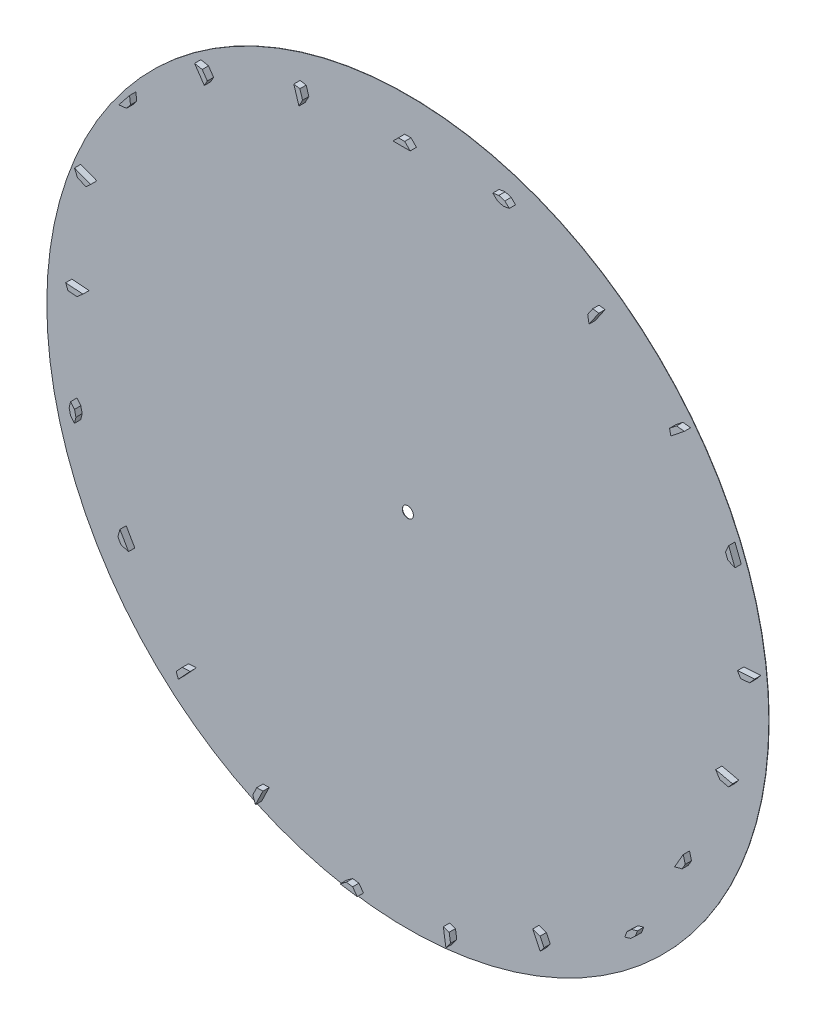
SolidWorks part; units mm, degrees
ref_plane "Front Plane" through (0, 0, 0) normal (0, 0, 1) x (1, 0, 0)
ref_plane "Top Plane" through (0, 0, 0) normal (0, 1, 0) x (1, 0, 0)
ref_plane "Right Plane" through (0, 0, 0) normal (1, 0, 0) x (0, 0, -1)
sketch "Sketch1" plane through (0, 0, 0) normal (0, 0, 1) x (1, 0, 0)
  line L0 (0, 0) -> (0, 115) construction
  circle A0 centre (0, 0) radius 115
  circle A1 centre (0, 0) radius 1.75
  dimension "D1" = 3.5
  dimension "D2" = 230
extrude "Boss-Extrude1" add sketch "Sketch1" along normal blind 0.1
sketch "Sketch2" plane through (0, 0, 0.1) normal (0, 0, 1) x (1, 0, 0)
  line L0 (0, 0) -> (0, 115) construction
  line L1 (0, 0) -> (6.8775, 114.7942) construction
  line L2 (0, 0) -> (13.7303, 114.1774) construction
  line L3 (0, 0) -> (20.534, 113.1519) construction
  line L4 (0, 0) -> (27.2642, 111.7214) construction
  line L5 (0, 0) -> (33.8968, 109.8909) construction
  line L6 (0, 0) -> (40.4081, 107.667) construction
  line L7 (0, 0) -> (46.7747, 105.0577) construction
  line L8 (0, 0) -> (52.9739, 102.0724) construction
  line L9 (0, 0) -> (58.9834, 98.7216) construction
  line L10 (0, 0) -> (64.7818, 95.0175) construction
  line L11 (0, 0) -> (70.3483, 90.9732) construction
  line L12 (0, 0) -> (75.663, 86.6032) construction
  line L13 (0, 0) -> (80.7068, 81.9233) construction
  line L14 (0, 0) -> (85.4617, 76.95) construction
  line L15 (0, 0) -> (89.9106, 71.7013) construction
  line L16 (0, 0) -> (94.0377, 66.196) construction
  line L17 (0, 0) -> (97.8282, 60.4536) construction
  line L18 (0, 0) -> (101.2685, 54.4949) construction
  line L19 (0, 0) -> (104.3462, 48.3411) construction
  line L20 (0, 0) -> (107.0505, 42.0142) construction
  line L21 (0, 0) -> (109.3715, 35.537) construction
  line L22 (0, 0) -> (111.301, 28.9325) construction
  line L23 (0, 0) -> (112.8321, 22.2244) construction
  line L24 (0, 0) -> (113.9592, 15.4368) construction
  line L25 (0, 0) -> (114.6784, 8.594) construction
  line L26 (0, 0) -> (114.9871, 1.7203) construction
  line L27 (0, 0) -> (114.8842, -5.1595) construction
  line L28 (0, 0) -> (114.37, -12.0208) construction
  line L29 (0, 0) -> (113.4464, -18.8391) construction
  line L30 (0, 0) -> (112.1167, -25.5899) construction
  line L31 (0, 0) -> (110.3857, -32.2491) construction
  line L32 (0, 0) -> (108.2594, -38.7929) construction
  line L33 (0, 0) -> (105.7457, -45.1979) construction
  line L34 (0, 0) -> (102.8534, -51.441) construction
  line L35 (0, 0) -> (99.5929, -57.5) construction
  line L36 (0, 0) -> (95.9759, -63.3532) construction
  line L37 (0, 0) -> (92.0154, -68.9795) construction
  line L38 (0, 0) -> (87.7254, -74.359) construction
  line L39 (0, 0) -> (83.1214, -79.4722) construction
  line L40 (0, 0) -> (78.2199, -84.301) construction
  line L41 (0, 0) -> (73.0383, -88.828) construction
  line L42 (0, 0) -> (67.5953, -93.037) construction
  line L43 (0, 0) -> (61.9103, -96.9129) construction
  line L44 (0, 0) -> (56.0037, -100.4419) construction
  line L45 (0, 0) -> (49.8966, -103.6114) construction
  line L46 (0, 0) -> (43.6109, -106.41) construction
  line L47 (0, 0) -> (37.1691, -108.8276) construction
  line L48 (0, 0) -> (30.5942, -110.8557) construction
  line L49 (0, 0) -> (23.9098, -112.487) construction
  line L50 (0, 0) -> (17.1399, -113.7155) construction
  line L51 (0, 0) -> (10.3085, -114.537) construction
  line L52 (0, 0) -> (3.4403, -114.9485) construction
  line L53 (0, 0) -> (-3.4403, -114.9485) construction
  line L54 (0, 0) -> (-10.3085, -114.537) construction
  line L55 (0, 0) -> (-17.1399, -113.7155) construction
  line L56 (0, 0) -> (-23.9098, -112.487) construction
  line L57 (0, 0) -> (-30.5942, -110.8557) construction
  line L58 (0, 0) -> (-37.1691, -108.8276) construction
  line L59 (0, 0) -> (-43.6109, -106.41) construction
  line L60 (0, 0) -> (-49.8966, -103.6114) construction
  line L61 (0, 0) -> (-56.0037, -100.4419) construction
  line L62 (0, 0) -> (-61.9103, -96.9129) construction
  line L63 (0, 0) -> (-67.5953, -93.037) construction
  line L64 (0, 0) -> (-73.0383, -88.828) construction
  line L65 (0, 0) -> (-78.2199, -84.301) construction
  line L66 (0, 0) -> (-83.1214, -79.4722) construction
  line L67 (0, 0) -> (-87.7254, -74.359) construction
  line L68 (0, 0) -> (-92.0154, -68.9795) construction
  line L69 (0, 0) -> (-95.9759, -63.3532) construction
  line L70 (0, 0) -> (-99.5929, -57.5) construction
  line L71 (0, 0) -> (-102.8534, -51.441) construction
  line L72 (0, 0) -> (-105.7457, -45.1979) construction
  line L73 (0, 0) -> (-108.2594, -38.7929) construction
  line L74 (0, 0) -> (-110.3857, -32.2491) construction
  line L75 (0, 0) -> (-112.1167, -25.5899) construction
  line L76 (0, 0) -> (-113.4464, -18.8391) construction
  line L77 (0, 0) -> (-114.37, -12.0208) construction
  line L78 (0, 0) -> (-114.8842, -5.1595) construction
  line L79 (0, 0) -> (-114.9871, 1.7203) construction
  line L80 (0, 0) -> (-114.6784, 8.594) construction
  line L81 (0, 0) -> (-113.9592, 15.4368) construction
  line L82 (0, 0) -> (-112.8321, 22.2244) construction
  line L83 (0, 0) -> (-111.301, 28.9325) construction
  line L84 (0, 0) -> (-109.3715, 35.537) construction
  line L85 (0, 0) -> (-107.0505, 42.0142) construction
  line L86 (0, 0) -> (-104.3462, 48.3411) construction
  line L87 (0, 0) -> (-101.2685, 54.4949) construction
  line L88 (0, 0) -> (-97.8282, 60.4536) construction
  line L89 (0, 0) -> (-94.0377, 66.196) construction
  line L90 (0, 0) -> (-89.9106, 71.7013) construction
  line L91 (0, 0) -> (-85.4617, 76.95) construction
  line L92 (0, 0) -> (-80.7068, 81.9233) construction
  line L93 (0, 0) -> (-75.663, 86.6032) construction
  line L94 (0, 0) -> (-70.3483, 90.9732) construction
  line L95 (0, 0) -> (-64.7818, 95.0175) construction
  line L96 (0, 0) -> (-58.9834, 98.7216) construction
  line L97 (0, 0) -> (-52.9739, 102.0724) construction
  line L98 (0, 0) -> (-46.7747, 105.0577) construction
  line L99 (0, 0) -> (-40.4081, 107.667) construction
  line L100 (0, 0) -> (-33.8968, 109.8909) construction
  line L101 (0, 0) -> (-27.2642, 111.7214) construction
  line L102 (0, 0) -> (-20.534, 113.1519) construction
  line L103 (0, 0) -> (-13.7303, 114.1774) construction
  line L104 (0, 0) -> (-6.8775, 114.7942) construction
  line L105 (-2.75, 113) -> (2.75, 113)
  line L106 (-2.75, 113) -> (2.75, 113) construction
  line L107 (-2.75, 113) -> (-2.75, 102) construction
  line L108 (-2.75, 102) -> (2.75, 102) construction
  line L109 (2.75, 113) -> (2.75, 102) construction
  line L110 (-1, 111.25) -> (1, 111.25) construction
  line L111 (-1, 111.25) -> (-1, 103.75) construction
  line L112 (-1, 103.75) -> (1, 103.75) construction
  line L113 (1, 111.25) -> (1, 103.75) construction
  line L114 (-1, 108.375) -> (1, 108.375) construction
  line L115 (-1, 108.375) -> (-1, 106.625) construction
  line L116 (-1, 106.625) -> (1, 106.625) construction
  line L117 (1, 108.375) -> (1, 106.625) construction
  line L118 (2.75, 113) -> (1, 111.25)
  line L119 (1, 111.25) -> (-1, 111.25)
  line L120 (-1, 111.25) -> (-2.75, 113)
  line L121 (-1, 108.375) -> (-2.75, 107.5)
  line L122 (-2.75, 107.5) -> (-1, 106.625)
  line L123 (-1, 106.625) -> (1, 106.625)
  line L124 (1, 106.625) -> (2.75, 107.5)
  line L125 (2.75, 107.5) -> (1, 108.375)
  line L126 (1, 108.375) -> (-1, 108.375)
  line L127 (-2.75, 113) -> (-2.75, 107.5)
  line L128 (-1, 111.25) -> (-1, 108.375)
  line L129 (1, 111.25) -> (1, 108.375)
  line L130 (2.75, 113) -> (2.75, 107.5)
  line L131 (-1, 103.75) -> (-2.75, 102)
  line L132 (-2.75, 102) -> (2.75, 102)
  line L133 (2.75, 102) -> (1, 103.75)
  line L134 (1, 103.75) -> (-1, 103.75)
  line L135 (-1, 103.75) -> (-1, 106.625)
  line L136 (-2.75, 107.5) -> (-2.75, 102)
  line L137 (2.75, 107.5) -> (2.75, 102)
  line L138 (1, 106.625) -> (1, 103.75)
  line L139 (30.6795, 108.7903) -> (35.9352, 107.1692)
  line L140 (31.8359, 106.6022) -> (30.6795, 108.7903)
  line L141 (35.9352, 107.1692) -> (33.7471, 106.0127)
  line L142 (33.7471, 106.0127) -> (31.8359, 106.6022)
  line L143 (31.8359, 106.6022) -> (30.9885, 103.855)
  line L144 (30.6795, 108.7903) -> (29.0584, 103.5347)
  line L145 (30.9885, 103.855) -> (29.0584, 103.5347)
  line L146 (29.0584, 103.5347) -> (27.4372, 98.279)
  line L147 (29.0584, 103.5347) -> (30.4727, 102.1827)
  line L148 (29.6253, 99.4354) -> (27.4372, 98.279)
  line L149 (27.4372, 98.279) -> (32.6929, 96.6578)
  line L150 (31.5364, 98.8459) -> (29.6253, 99.4354)
  line L151 (32.6929, 96.6578) -> (31.5364, 98.8459)
  line L152 (34.314, 101.9135) -> (32.6929, 96.6578)
  line L153 (30.4727, 102.1827) -> (32.3838, 101.5932)
  line L154 (29.6253, 99.4354) -> (30.4727, 102.1827)
  line L155 (32.3838, 101.5932) -> (31.5364, 98.8459)
  line L156 (32.3838, 101.5932) -> (34.314, 101.9135)
  line L157 (34.314, 101.9135) -> (32.8997, 103.2654)
  line L158 (35.9352, 107.1692) -> (34.314, 101.9135)
  line L159 (33.7471, 106.0127) -> (32.8997, 103.2654)
  line L160 (32.8997, 103.2654) -> (30.9885, 103.855)
  line L161 (61.383, 94.9141) -> (65.9273, 91.8159)
  line L162 (61.8431, 92.4824) -> (61.383, 94.9141)
  line L163 (65.9273, 91.8159) -> (63.4956, 91.3557)
  line L164 (63.4956, 91.3557) -> (61.8431, 92.4824)
  line L165 (61.8431, 92.4824) -> (60.2236, 90.1069)
  line L166 (61.383, 94.9141) -> (58.2847, 90.3698)
  line L167 (60.2236, 90.1069) -> (58.2847, 90.3698)
  line L168 (58.2847, 90.3698) -> (55.1865, 85.8255)
  line L169 (58.2847, 90.3698) -> (59.2378, 88.661)
  line L170 (57.6182, 86.2856) -> (55.1865, 85.8255)
  line L171 (55.1865, 85.8255) -> (59.7308, 82.7272)
  line L172 (59.2707, 85.159) -> (57.6182, 86.2856)
  line L173 (59.7308, 82.7272) -> (59.2707, 85.159)
  line L174 (62.8291, 87.2715) -> (59.7308, 82.7272)
  line L175 (59.2378, 88.661) -> (60.8902, 87.5344)
  line L176 (57.6182, 86.2856) -> (59.2378, 88.661)
  line L177 (60.8902, 87.5344) -> (59.2707, 85.159)
  line L178 (60.8902, 87.5344) -> (62.8291, 87.2715)
  line L179 (62.8291, 87.2715) -> (61.8761, 88.9803)
  line L180 (65.9273, 91.8159) -> (62.8291, 87.2715)
  line L181 (63.4956, 91.3557) -> (61.8761, 88.9803)
  line L182 (61.8761, 88.9803) -> (60.2236, 90.1069)
  line L183 (86.6324, 72.6044) -> (90.0616, 68.3043)
  line L184 (86.3553, 70.1451) -> (86.6324, 72.6044)
  line L185 (90.0616, 68.3043) -> (87.6022, 68.5814)
  line L186 (87.6022, 68.5814) -> (86.3553, 70.1451)
  line L187 (86.3553, 70.1451) -> (84.1075, 68.3525)
  line L188 (86.6324, 72.6044) -> (82.3323, 69.1752)
  line L189 (84.1075, 68.3525) -> (82.3323, 69.1752)
  line L190 (82.3323, 69.1752) -> (78.0322, 65.746)
  line L191 (82.3323, 69.1752) -> (82.7393, 67.2614)
  line L192 (80.4915, 65.4689) -> (78.0322, 65.746)
  line L193 (78.0322, 65.746) -> (81.4614, 61.4459)
  line L194 (81.7385, 63.9052) -> (80.4915, 65.4689)
  line L195 (81.4614, 61.4459) -> (81.7385, 63.9052)
  line L196 (85.7615, 64.8751) -> (81.4614, 61.4459)
  line L197 (82.7393, 67.2614) -> (83.9863, 65.6978)
  line L198 (80.4915, 65.4689) -> (82.7393, 67.2614)
  line L199 (83.9863, 65.6978) -> (81.7385, 63.9052)
  line L200 (83.9863, 65.6978) -> (85.7615, 64.8751)
  line L201 (85.7615, 64.8751) -> (85.3545, 66.7889)
  line L202 (90.0616, 68.3043) -> (85.7615, 64.8751)
  line L203 (87.6022, 68.5814) -> (85.3545, 66.7889)
  line L204 (85.3545, 66.7889) -> (84.1075, 68.3525)
  line L205 (104.184, 43.8434) -> (106.1934, 38.7236)
  line L206 (103.1944, 41.5751) -> (104.184, 43.8434)
  line L207 (106.1934, 38.7236) -> (103.925, 39.7133)
  line L208 (103.925, 39.7133) -> (103.1944, 41.5751)
  line L209 (103.1944, 41.5751) -> (100.5181, 40.5247)
  line L210 (104.184, 43.8434) -> (99.0642, 41.8341)
  line L211 (100.5181, 40.5247) -> (99.0642, 41.8341)
  line L212 (99.0642, 41.8341) -> (93.9444, 39.8247)
  line L213 (99.0642, 41.8341) -> (98.8891, 39.8854)
  line L214 (96.2128, 38.835) -> (93.9444, 39.8247)
  line L215 (93.9444, 39.8247) -> (95.9538, 34.7049)
  line L216 (96.9435, 36.9733) -> (96.2128, 38.835)
  line L217 (95.9538, 34.7049) -> (96.9435, 36.9733)
  line L218 (101.0736, 36.7143) -> (95.9538, 34.7049)
  line L219 (98.8891, 39.8854) -> (99.6198, 38.0236)
  line L220 (96.2128, 38.835) -> (98.8891, 39.8854)
  line L221 (99.6198, 38.0236) -> (96.9435, 36.9733)
  line L222 (99.6198, 38.0236) -> (101.0736, 36.7143)
  line L223 (101.0736, 36.7143) -> (101.2488, 38.663)
  line L224 (106.1934, 38.7236) -> (101.0736, 36.7143)
  line L225 (103.925, 39.7133) -> (101.2488, 38.663)
  line L226 (101.2488, 38.663) -> (100.5181, 40.5247)
  line L227 (112.4785, 11.1868) -> (112.8895, 5.7022)
  line L228 (110.8642, 9.3109) -> (112.4785, 11.1868)
  line L229 (112.8895, 5.7022) -> (111.0137, 7.3165)
  line L230 (111.0137, 7.3165) -> (110.8642, 9.3109)
  line L231 (110.8642, 9.3109) -> (107.9972, 9.0961)
  line L232 (112.4785, 11.1868) -> (106.9939, 10.7758)
  line L233 (107.9972, 9.0961) -> (106.9939, 10.7758)
  line L234 (106.9939, 10.7758) -> (101.5093, 10.3648)
  line L235 (106.9939, 10.7758) -> (106.2521, 8.9653)
  line L236 (103.3852, 8.7505) -> (101.5093, 10.3648)
  line L237 (101.5093, 10.3648) -> (101.9203, 4.8802)
  line L238 (103.5346, 6.756) -> (103.3852, 8.7505)
  line L239 (101.9203, 4.8802) -> (103.5346, 6.756)
  line L240 (107.4049, 5.2912) -> (101.9203, 4.8802)
  line L241 (106.2521, 8.9653) -> (106.4016, 6.9709)
  line L242 (103.3852, 8.7505) -> (106.2521, 8.9653)
  line L243 (106.4016, 6.9709) -> (103.5346, 6.756)
  line L244 (106.4016, 6.9709) -> (107.4049, 5.2912)
  line L245 (107.4049, 5.2912) -> (108.1467, 7.1017)
  line L246 (112.8895, 5.7022) -> (107.4049, 5.2912)
  line L247 (111.0137, 7.3165) -> (108.1467, 7.1017)
  line L248 (108.1467, 7.1017) -> (107.9972, 9.0961)
  line L249 (110.7788, -22.4638) -> (109.5549, -27.8259)
  line L250 (108.6833, -23.7805) -> (110.7788, -22.4638)
  line L251 (109.5549, -27.8259) -> (108.2382, -25.7304)
  line L252 (108.2382, -25.7304) -> (108.6833, -23.7805)
  line L253 (108.6833, -23.7805) -> (105.8803, -23.1408)
  line L254 (110.7788, -22.4638) -> (105.4167, -21.2399)
  line L255 (105.8803, -23.1408) -> (105.4167, -21.2399)
  line L256 (105.4167, -21.2399) -> (100.0546, -20.0161)
  line L257 (105.4167, -21.2399) -> (104.1742, -22.7514)
  line L258 (101.3713, -22.1116) -> (100.0546, -20.0161)
  line L259 (100.0546, -20.0161) -> (98.8307, -25.3782)
  line L260 (100.9262, -24.0615) -> (101.3713, -22.1116)
  line L261 (98.8307, -25.3782) -> (100.9262, -24.0615)
  line L262 (104.1928, -26.6021) -> (98.8307, -25.3782)
  line L263 (104.1742, -22.7514) -> (103.7292, -24.7012)
  line L264 (101.3713, -22.1116) -> (104.1742, -22.7514)
  line L265 (103.7292, -24.7012) -> (100.9262, -24.0615)
  line L266 (103.7292, -24.7012) -> (104.1928, -26.6021)
  line L267 (104.1928, -26.6021) -> (105.4353, -25.0906)
  line L268 (109.5549, -27.8259) -> (104.1928, -26.6021)
  line L269 (108.2382, -25.7304) -> (105.4353, -25.0906)
  line L270 (105.4353, -25.0906) -> (105.8803, -23.1408)
  line L271 (99.2359, -54.1184) -> (96.4859, -58.8816)
  line L272 (96.8453, -54.759) -> (99.2359, -54.1184)
  line L273 (96.4859, -58.8816) -> (95.8453, -56.491)
  line L274 (95.8453, -56.491) -> (96.8453, -54.759)
  line L275 (96.8453, -54.759) -> (94.3555, -53.3215)
  line L276 (99.2359, -54.1184) -> (94.4727, -51.3684)
  line L277 (94.3555, -53.3215) -> (94.4727, -51.3684)
  line L278 (94.4727, -51.3684) -> (89.7096, -48.6184)
  line L279 (94.4727, -51.3684) -> (92.84, -52.4465)
  line L280 (90.3501, -51.009) -> (89.7096, -48.6184)
  line L281 (89.7096, -48.6184) -> (86.9596, -53.3816)
  line L282 (89.3501, -52.741) -> (90.3501, -51.009)
  line L283 (86.9596, -53.3816) -> (89.3501, -52.741)
  line L284 (91.7227, -56.1316) -> (86.9596, -53.3816)
  line L285 (92.84, -52.4465) -> (91.84, -54.1785)
  line L286 (90.3501, -51.009) -> (92.84, -52.4465)
  line L287 (91.84, -54.1785) -> (89.3501, -52.741)
  line L288 (91.84, -54.1785) -> (91.7227, -56.1316)
  line L289 (91.7227, -56.1316) -> (93.3555, -55.0535)
  line L290 (96.4859, -58.8816) -> (91.7227, -56.1316)
  line L291 (95.8453, -56.491) -> (93.3555, -55.0535)
  line L292 (93.3555, -55.0535) -> (94.3555, -53.3215)
  line L293 (78.8754, -80.9644) -> (74.8436, -84.7053)
  line L294 (76.4023, -80.8718) -> (78.8754, -80.9644)
  line L295 (74.8436, -84.7053) -> (74.9362, -82.2322)
  line L296 (74.9362, -82.2322) -> (76.4023, -80.8718)
  line L297 (76.4023, -80.8718) -> (74.4468, -78.7643)
  line L298 (78.8754, -80.9644) -> (75.1345, -76.9326)
  line L299 (74.4468, -78.7643) -> (75.1345, -76.9326)
  line L300 (75.1345, -76.9326) -> (71.3935, -72.9008)
  line L301 (75.1345, -76.9326) -> (73.2565, -77.4815)
  line L302 (71.301, -75.374) -> (71.3935, -72.9008)
  line L303 (71.3935, -72.9008) -> (67.3617, -76.6418)
  line L304 (69.8349, -76.7343) -> (71.301, -75.374)
  line L305 (67.3617, -76.6418) -> (69.8349, -76.7343)
  line L306 (71.1027, -80.6736) -> (67.3617, -76.6418)
  line L307 (73.2565, -77.4815) -> (71.7904, -78.8418)
  line L308 (71.301, -75.374) -> (73.2565, -77.4815)
  line L309 (71.7904, -78.8418) -> (69.8349, -76.7343)
  line L310 (71.7904, -78.8418) -> (71.1027, -80.6736)
  line L311 (71.1027, -80.6736) -> (72.9807, -80.1247)
  line L312 (74.8436, -84.7053) -> (71.1027, -80.6736)
  line L313 (74.9362, -82.2322) -> (72.9807, -80.1247)
  line L314 (72.9807, -80.1247) -> (74.4468, -78.7643)
  line L315 (51.5065, -100.6163) -> (46.5512, -103.0027)
  line L316 (49.1705, -99.7989) -> (51.5065, -100.6163)
  line L317 (46.5512, -103.0027) -> (47.3686, -100.6667)
  line L318 (47.3686, -100.6667) -> (49.1705, -99.7989)
  line L319 (49.1705, -99.7989) -> (47.9231, -97.2086)
  line L320 (51.5065, -100.6163) -> (49.1202, -95.661)
  line L321 (47.9231, -97.2086) -> (49.1202, -95.661)
  line L322 (49.1202, -95.661) -> (46.7338, -90.7056)
  line L323 (49.1202, -95.661) -> (47.1638, -95.6319)
  line L324 (45.9164, -93.0416) -> (46.7338, -90.7056)
  line L325 (46.7338, -90.7056) -> (41.7785, -93.092)
  line L326 (44.1145, -93.9094) -> (45.9164, -93.0416)
  line L327 (41.7785, -93.092) -> (44.1145, -93.9094)
  line L328 (44.1648, -98.0473) -> (41.7785, -93.092)
  line L329 (47.1638, -95.6319) -> (45.3619, -96.4997)
  line L330 (45.9164, -93.0416) -> (47.1638, -95.6319)
  line L331 (45.3619, -96.4997) -> (44.1145, -93.9094)
  line L332 (45.3619, -96.4997) -> (44.1648, -98.0473)
  line L333 (44.1648, -98.0473) -> (46.1212, -98.0764)
  line L334 (46.5512, -103.0027) -> (44.1648, -98.0473)
  line L335 (47.3686, -100.6667) -> (46.1212, -98.0764)
  line L336 (46.1212, -98.0764) -> (47.9231, -97.2086)
  line L337 (19.5611, -111.328) -> (14.1225, -112.1477)
  line L338 (17.5698, -109.8584) -> (19.5611, -111.328)
  line L339 (14.1225, -112.1477) -> (15.5921, -110.1565)
  line L340 (15.5921, -110.1565) -> (17.5698, -109.8584)
  line L341 (17.5698, -109.8584) -> (17.1413, -107.0155)
  line L342 (19.5611, -111.328) -> (18.7413, -105.8894)
  line L343 (17.1413, -107.0155) -> (18.7413, -105.8894)
  line L344 (18.7413, -105.8894) -> (17.9216, -100.4509)
  line L345 (18.7413, -105.8894) -> (16.8805, -105.285)
  line L346 (16.452, -102.4422) -> (17.9216, -100.4509)
  line L347 (17.9216, -100.4509) -> (12.483, -101.2706)
  line L348 (14.4743, -102.7402) -> (16.452, -102.4422)
  line L349 (12.483, -101.2706) -> (14.4743, -102.7402)
  line L350 (13.3028, -106.7092) -> (12.483, -101.2706)
  line L351 (16.8805, -105.285) -> (14.9028, -105.5831)
  line L352 (16.452, -102.4422) -> (16.8805, -105.285)
  line L353 (14.9028, -105.5831) -> (14.4743, -102.7402)
  line L354 (14.9028, -105.5831) -> (13.3028, -106.7092)
  line L355 (13.3028, -106.7092) -> (15.1636, -107.3136)
  line L356 (14.1225, -112.1477) -> (13.3028, -106.7092)
  line L357 (15.5921, -110.1565) -> (15.1636, -107.3136)
  line L358 (15.1636, -107.3136) -> (17.1413, -107.0155)
  line L359 (-14.1225, -112.1477) -> (-19.5611, -111.328)
  line L360 (-15.5921, -110.1565) -> (-14.1225, -112.1477)
  line L361 (-19.5611, -111.328) -> (-17.5698, -109.8584)
  line L362 (-17.5698, -109.8584) -> (-15.5921, -110.1565)
  line L363 (-15.5921, -110.1565) -> (-15.1636, -107.3136)
  line L364 (-14.1225, -112.1477) -> (-13.3028, -106.7092)
  line L365 (-15.1636, -107.3136) -> (-13.3028, -106.7092)
  line L366 (-13.3028, -106.7092) -> (-12.483, -101.2706)
  line L367 (-13.3028, -106.7092) -> (-14.9028, -105.5831)
  line L368 (-14.4743, -102.7402) -> (-12.483, -101.2706)
  line L369 (-12.483, -101.2706) -> (-17.9216, -100.4509)
  line L370 (-16.452, -102.4422) -> (-14.4743, -102.7402)
  line L371 (-17.9216, -100.4509) -> (-16.452, -102.4422)
  line L372 (-18.7413, -105.8894) -> (-17.9216, -100.4509)
  line L373 (-14.9028, -105.5831) -> (-16.8805, -105.285)
  line L374 (-14.4743, -102.7402) -> (-14.9028, -105.5831)
  line L375 (-16.8805, -105.285) -> (-16.452, -102.4422)
  line L376 (-16.8805, -105.285) -> (-18.7413, -105.8894)
  line L377 (-18.7413, -105.8894) -> (-17.1413, -107.0155)
  line L378 (-19.5611, -111.328) -> (-18.7413, -105.8894)
  line L379 (-17.5698, -109.8584) -> (-17.1413, -107.0155)
  line L380 (-17.1413, -107.0155) -> (-15.1636, -107.3136)
  line L381 (-46.5512, -103.0027) -> (-51.5065, -100.6163)
  line L382 (-47.3686, -100.6667) -> (-46.5512, -103.0027)
  line L383 (-51.5065, -100.6163) -> (-49.1705, -99.7989)
  line L384 (-49.1705, -99.7989) -> (-47.3686, -100.6667)
  line L385 (-47.3686, -100.6667) -> (-46.1212, -98.0764)
  line L386 (-46.5512, -103.0027) -> (-44.1648, -98.0473)
  line L387 (-46.1212, -98.0764) -> (-44.1648, -98.0473)
  line L388 (-44.1648, -98.0473) -> (-41.7785, -93.092)
  line L389 (-44.1648, -98.0473) -> (-45.3619, -96.4997)
  line L390 (-44.1145, -93.9094) -> (-41.7785, -93.092)
  line L391 (-41.7785, -93.092) -> (-46.7338, -90.7056)
  line L392 (-45.9164, -93.0416) -> (-44.1145, -93.9094)
  line L393 (-46.7338, -90.7056) -> (-45.9164, -93.0416)
  line L394 (-49.1202, -95.661) -> (-46.7338, -90.7056)
  line L395 (-45.3619, -96.4997) -> (-47.1638, -95.6319)
  line L396 (-44.1145, -93.9094) -> (-45.3619, -96.4997)
  line L397 (-47.1638, -95.6319) -> (-45.9164, -93.0416)
  line L398 (-47.1638, -95.6319) -> (-49.1202, -95.661)
  line L399 (-49.1202, -95.661) -> (-47.9231, -97.2086)
  line L400 (-51.5065, -100.6163) -> (-49.1202, -95.661)
  line L401 (-49.1705, -99.7989) -> (-47.9231, -97.2086)
  line L402 (-47.9231, -97.2086) -> (-46.1212, -98.0764)
  line L403 (-74.8436, -84.7053) -> (-78.8754, -80.9644)
  line L404 (-74.9362, -82.2322) -> (-74.8436, -84.7053)
  line L405 (-78.8754, -80.9644) -> (-76.4023, -80.8718)
  line L406 (-76.4023, -80.8718) -> (-74.9362, -82.2322)
  line L407 (-74.9362, -82.2322) -> (-72.9807, -80.1247)
  line L408 (-74.8436, -84.7053) -> (-71.1027, -80.6736)
  line L409 (-72.9807, -80.1247) -> (-71.1027, -80.6736)
  line L410 (-71.1027, -80.6736) -> (-67.3617, -76.6418)
  line L411 (-71.1027, -80.6736) -> (-71.7904, -78.8418)
  line L412 (-69.8349, -76.7343) -> (-67.3617, -76.6418)
  line L413 (-67.3617, -76.6418) -> (-71.3935, -72.9008)
  line L414 (-71.301, -75.374) -> (-69.8349, -76.7343)
  line L415 (-71.3935, -72.9008) -> (-71.301, -75.374)
  line L416 (-75.1345, -76.9326) -> (-71.3935, -72.9008)
  line L417 (-71.7904, -78.8418) -> (-73.2565, -77.4815)
  line L418 (-69.8349, -76.7343) -> (-71.7904, -78.8418)
  line L419 (-73.2565, -77.4815) -> (-71.301, -75.374)
  line L420 (-73.2565, -77.4815) -> (-75.1345, -76.9326)
  line L421 (-75.1345, -76.9326) -> (-74.4468, -78.7643)
  line L422 (-78.8754, -80.9644) -> (-75.1345, -76.9326)
  line L423 (-76.4023, -80.8718) -> (-74.4468, -78.7643)
  line L424 (-74.4468, -78.7643) -> (-72.9807, -80.1247)
  line L425 (-96.4859, -58.8816) -> (-99.2359, -54.1184)
  line L426 (-95.8453, -56.491) -> (-96.4859, -58.8816)
  line L427 (-99.2359, -54.1184) -> (-96.8453, -54.759)
  line L428 (-96.8453, -54.759) -> (-95.8453, -56.491)
  line L429 (-95.8453, -56.491) -> (-93.3555, -55.0535)
  line L430 (-96.4859, -58.8816) -> (-91.7227, -56.1316)
  line L431 (-93.3555, -55.0535) -> (-91.7227, -56.1316)
  line L432 (-91.7227, -56.1316) -> (-86.9596, -53.3816)
  line L433 (-91.7227, -56.1316) -> (-91.84, -54.1785)
  line L434 (-89.3501, -52.741) -> (-86.9596, -53.3816)
  line L435 (-86.9596, -53.3816) -> (-89.7096, -48.6184)
  line L436 (-90.3501, -51.009) -> (-89.3501, -52.741)
  line L437 (-89.7096, -48.6184) -> (-90.3501, -51.009)
  line L438 (-94.4727, -51.3684) -> (-89.7096, -48.6184)
  line L439 (-91.84, -54.1785) -> (-92.84, -52.4465)
  line L440 (-89.3501, -52.741) -> (-91.84, -54.1785)
  line L441 (-92.84, -52.4465) -> (-90.3501, -51.009)
  line L442 (-92.84, -52.4465) -> (-94.4727, -51.3684)
  line L443 (-94.4727, -51.3684) -> (-94.3555, -53.3215)
  line L444 (-99.2359, -54.1184) -> (-94.4727, -51.3684)
  line L445 (-96.8453, -54.759) -> (-94.3555, -53.3215)
  line L446 (-94.3555, -53.3215) -> (-93.3555, -55.0535)
  line L447 (-109.5549, -27.8259) -> (-110.7788, -22.4638)
  line L448 (-108.2382, -25.7304) -> (-109.5549, -27.8259)
  line L449 (-110.7788, -22.4638) -> (-108.6833, -23.7805)
  line L450 (-108.6833, -23.7805) -> (-108.2382, -25.7304)
  line L451 (-108.2382, -25.7304) -> (-105.4353, -25.0906)
  line L452 (-109.5549, -27.8259) -> (-104.1928, -26.6021)
  line L453 (-105.4353, -25.0906) -> (-104.1928, -26.6021)
  line L454 (-104.1928, -26.6021) -> (-98.8307, -25.3782)
  line L455 (-104.1928, -26.6021) -> (-103.7292, -24.7012)
  line L456 (-100.9262, -24.0615) -> (-98.8307, -25.3782)
  line L457 (-98.8307, -25.3782) -> (-100.0546, -20.0161)
  line L458 (-101.3713, -22.1116) -> (-100.9262, -24.0615)
  line L459 (-100.0546, -20.0161) -> (-101.3713, -22.1116)
  line L460 (-105.4167, -21.2399) -> (-100.0546, -20.0161)
  line L461 (-103.7292, -24.7012) -> (-104.1742, -22.7514)
  line L462 (-100.9262, -24.0615) -> (-103.7292, -24.7012)
  line L463 (-104.1742, -22.7514) -> (-101.3713, -22.1116)
  line L464 (-104.1742, -22.7514) -> (-105.4167, -21.2399)
  line L465 (-105.4167, -21.2399) -> (-105.8803, -23.1408)
  line L466 (-110.7788, -22.4638) -> (-105.4167, -21.2399)
  line L467 (-108.6833, -23.7805) -> (-105.8803, -23.1408)
  line L468 (-105.8803, -23.1408) -> (-105.4353, -25.0906)
  line L469 (-112.8895, 5.7022) -> (-112.4785, 11.1868)
  line L470 (-111.0137, 7.3165) -> (-112.8895, 5.7022)
  line L471 (-112.4785, 11.1868) -> (-110.8642, 9.3109)
  line L472 (-110.8642, 9.3109) -> (-111.0137, 7.3165)
  line L473 (-111.0137, 7.3165) -> (-108.1467, 7.1017)
  line L474 (-112.8895, 5.7022) -> (-107.4049, 5.2912)
  line L475 (-108.1467, 7.1017) -> (-107.4049, 5.2912)
  line L476 (-107.4049, 5.2912) -> (-101.9203, 4.8802)
  line L477 (-107.4049, 5.2912) -> (-106.4016, 6.9709)
  line L478 (-103.5346, 6.756) -> (-101.9203, 4.8802)
  line L479 (-101.9203, 4.8802) -> (-101.5093, 10.3648)
  line L480 (-103.3852, 8.7505) -> (-103.5346, 6.756)
  line L481 (-101.5093, 10.3648) -> (-103.3852, 8.7505)
  line L482 (-106.9939, 10.7758) -> (-101.5093, 10.3648)
  line L483 (-106.4016, 6.9709) -> (-106.2521, 8.9653)
  line L484 (-103.5346, 6.756) -> (-106.4016, 6.9709)
  line L485 (-106.2521, 8.9653) -> (-103.3852, 8.7505)
  line L486 (-106.2521, 8.9653) -> (-106.9939, 10.7758)
  line L487 (-106.9939, 10.7758) -> (-107.9972, 9.0961)
  line L488 (-112.4785, 11.1868) -> (-106.9939, 10.7758)
  line L489 (-110.8642, 9.3109) -> (-107.9972, 9.0961)
  line L490 (-107.9972, 9.0961) -> (-108.1467, 7.1017)
  line L491 (-106.1934, 38.7236) -> (-104.184, 43.8434)
  line L492 (-103.925, 39.7133) -> (-106.1934, 38.7236)
  line L493 (-104.184, 43.8434) -> (-103.1944, 41.5751)
  line L494 (-103.1944, 41.5751) -> (-103.925, 39.7133)
  line L495 (-103.925, 39.7133) -> (-101.2488, 38.663)
  line L496 (-106.1934, 38.7236) -> (-101.0736, 36.7143)
  line L497 (-101.2488, 38.663) -> (-101.0736, 36.7143)
  line L498 (-101.0736, 36.7143) -> (-95.9538, 34.7049)
  line L499 (-101.0736, 36.7143) -> (-99.6198, 38.0236)
  line L500 (-96.9435, 36.9733) -> (-95.9538, 34.7049)
  line L501 (-95.9538, 34.7049) -> (-93.9444, 39.8247)
  line L502 (-96.2128, 38.835) -> (-96.9435, 36.9733)
  line L503 (-93.9444, 39.8247) -> (-96.2128, 38.835)
  line L504 (-99.0642, 41.8341) -> (-93.9444, 39.8247)
  line L505 (-99.6198, 38.0236) -> (-98.8891, 39.8854)
  line L506 (-96.9435, 36.9733) -> (-99.6198, 38.0236)
  line L507 (-98.8891, 39.8854) -> (-96.2128, 38.835)
  line L508 (-98.8891, 39.8854) -> (-99.0642, 41.8341)
  line L509 (-99.0642, 41.8341) -> (-100.5181, 40.5247)
  line L510 (-104.184, 43.8434) -> (-99.0642, 41.8341)
  line L511 (-103.1944, 41.5751) -> (-100.5181, 40.5247)
  line L512 (-100.5181, 40.5247) -> (-101.2488, 38.663)
  line L513 (-90.0616, 68.3043) -> (-86.6324, 72.6044)
  line L514 (-87.6022, 68.5814) -> (-90.0616, 68.3043)
  line L515 (-86.6324, 72.6044) -> (-86.3553, 70.1451)
  line L516 (-86.3553, 70.1451) -> (-87.6022, 68.5814)
  line L517 (-87.6022, 68.5814) -> (-85.3545, 66.7889)
  line L518 (-90.0616, 68.3043) -> (-85.7615, 64.8751)
  line L519 (-85.3545, 66.7889) -> (-85.7615, 64.8751)
  line L520 (-85.7615, 64.8751) -> (-81.4614, 61.4459)
  line L521 (-85.7615, 64.8751) -> (-83.9863, 65.6978)
  line L522 (-81.7385, 63.9052) -> (-81.4614, 61.4459)
  line L523 (-81.4614, 61.4459) -> (-78.0322, 65.746)
  line L524 (-80.4915, 65.4689) -> (-81.7385, 63.9052)
  line L525 (-78.0322, 65.746) -> (-80.4915, 65.4689)
  line L526 (-82.3323, 69.1752) -> (-78.0322, 65.746)
  line L527 (-83.9863, 65.6978) -> (-82.7393, 67.2614)
  line L528 (-81.7385, 63.9052) -> (-83.9863, 65.6978)
  line L529 (-82.7393, 67.2614) -> (-80.4915, 65.4689)
  line L530 (-82.7393, 67.2614) -> (-82.3323, 69.1752)
  line L531 (-82.3323, 69.1752) -> (-84.1075, 68.3525)
  line L532 (-86.6324, 72.6044) -> (-82.3323, 69.1752)
  line L533 (-86.3553, 70.1451) -> (-84.1075, 68.3525)
  line L534 (-84.1075, 68.3525) -> (-85.3545, 66.7889)
  line L535 (-65.9273, 91.8159) -> (-61.383, 94.9141)
  line L536 (-63.4956, 91.3557) -> (-65.9273, 91.8159)
  line L537 (-61.383, 94.9141) -> (-61.8431, 92.4824)
  line L538 (-61.8431, 92.4824) -> (-63.4956, 91.3557)
  line L539 (-63.4956, 91.3557) -> (-61.8761, 88.9803)
  line L540 (-65.9273, 91.8159) -> (-62.8291, 87.2715)
  line L541 (-61.8761, 88.9803) -> (-62.8291, 87.2715)
  line L542 (-62.8291, 87.2715) -> (-59.7308, 82.7272)
  line L543 (-62.8291, 87.2715) -> (-60.8902, 87.5344)
  line L544 (-59.2707, 85.159) -> (-59.7308, 82.7272)
  line L545 (-59.7308, 82.7272) -> (-55.1865, 85.8255)
  line L546 (-57.6182, 86.2856) -> (-59.2707, 85.159)
  line L547 (-55.1865, 85.8255) -> (-57.6182, 86.2856)
  line L548 (-58.2847, 90.3698) -> (-55.1865, 85.8255)
  line L549 (-60.8902, 87.5344) -> (-59.2378, 88.661)
  line L550 (-59.2707, 85.159) -> (-60.8902, 87.5344)
  line L551 (-59.2378, 88.661) -> (-57.6182, 86.2856)
  line L552 (-59.2378, 88.661) -> (-58.2847, 90.3698)
  line L553 (-58.2847, 90.3698) -> (-60.2236, 90.1069)
  line L554 (-61.383, 94.9141) -> (-58.2847, 90.3698)
  line L555 (-61.8431, 92.4824) -> (-60.2236, 90.1069)
  line L556 (-60.2236, 90.1069) -> (-61.8761, 88.9803)
  line L557 (-35.9352, 107.1692) -> (-30.6795, 108.7903)
  line L558 (-33.7471, 106.0127) -> (-35.9352, 107.1692)
  line L559 (-30.6795, 108.7903) -> (-31.8359, 106.6022)
  line L560 (-31.8359, 106.6022) -> (-33.7471, 106.0127)
  line L561 (-33.7471, 106.0127) -> (-32.8997, 103.2654)
  line L562 (-35.9352, 107.1692) -> (-34.314, 101.9135)
  line L563 (-32.8997, 103.2654) -> (-34.314, 101.9135)
  line L564 (-34.314, 101.9135) -> (-32.6929, 96.6578)
  line L565 (-34.314, 101.9135) -> (-32.3838, 101.5932)
  line L566 (-31.5364, 98.8459) -> (-32.6929, 96.6578)
  line L567 (-32.6929, 96.6578) -> (-27.4372, 98.279)
  line L568 (-29.6253, 99.4354) -> (-31.5364, 98.8459)
  line L569 (-27.4372, 98.279) -> (-29.6253, 99.4354)
  line L570 (-29.0584, 103.5347) -> (-27.4372, 98.279)
  line L571 (-32.3838, 101.5932) -> (-30.4727, 102.1827)
  line L572 (-31.5364, 98.8459) -> (-32.3838, 101.5932)
  line L573 (-30.4727, 102.1827) -> (-29.6253, 99.4354)
  line L574 (-30.4727, 102.1827) -> (-29.0584, 103.5347)
  line L575 (-29.0584, 103.5347) -> (-30.9885, 103.855)
  line L576 (-30.6795, 108.7903) -> (-29.0584, 103.5347)
  line L577 (-31.8359, 106.6022) -> (-30.9885, 103.855)
  line L578 (-30.9885, 103.855) -> (-32.8997, 103.2654)
  circle A0 centre (0, 0) radius 115 construction
  point P111 (0, 0)
  point P115 (0, 102)
  point P124 (1, 107.5)
  point P125 (1, 107.5)
  point P411 (0, 0)
  dimension "D2" = 5.5
  dimension "D3" = 11
  dimension "D4" = 102
  dimension "D5" = 1.75
  dimension "D6" = 1.75
  dimension "D7" = 1.75
  dimension "D8" = 1.75
  dimension "D9" = 1.75
  dimension "D1" = 105
  dimension "D10" = 21
extrude "Boss-Extrude2" add sketch "Sketch2" along normal blind 2 contours L133 L134 L131 L132 | L566 L572 L565 L564 | L541 L539 L536 L540 | L516 L515 L513 L514 | L493 L511 L509 L510 | L486 L485 L481 L482 | L465 L468 L453 L455 L461 L464 | L435 L437 L436 L434 | L412 L418 L411 L410 | L387 L385 L382 L386 | L362 L361 L359 L360 | L339 L357 L355 L356 | L332 L331 L327 L328 | L311 L314 L299 L301 L307 L310 | L281 L283 L282 L280 | L258 L264 L257 L256 | L233 L231 L228 L232 | L208 L207 L205 L206 | L185 L203 L201 L202 | L178 L177 L173 L174 | L157 L160 L145 L147 L153 L156
